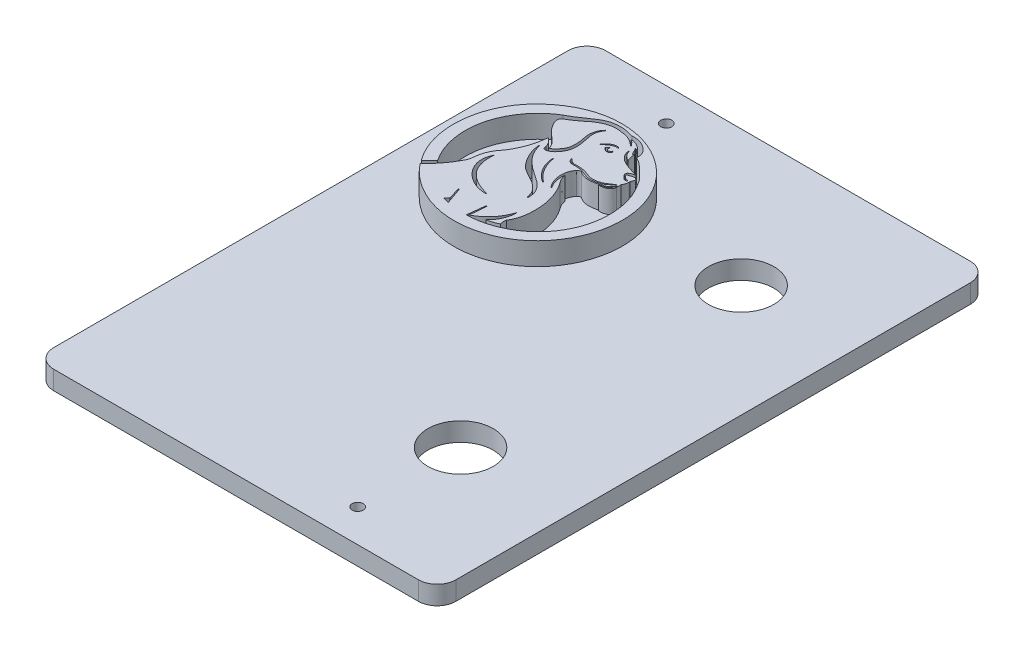
SolidWorks part; units mm, degrees
ref_plane "Alzado" through (0, 0, 0) normal (0, 0, 1) x (1, 0, 0)
ref_plane "Planta" through (0, 0, 0) normal (0, 1, 0) x (1, 0, 0)
ref_plane "Vista lateral" through (0, 0, 0) normal (1, 0, 0) x (0, 0, -1)
sketch "Croquis1" plane through (0, 0, 0) normal (0, 1, 0) x (1, 0, 0)
  line L1 (-19.5, 29.5) -> (19.5, 29.5)
  line L2 (-21.5, 27.5) -> (-21.5, -27.5)
  line L3 (-19.5, -29.5) -> (19.5, -29.5)
  line L4 (21.5, 27.5) -> (21.5, -27.5)
  arc A0 (-19.5, 29.5) -> (-21.5, 27.5) centre (-19.5, 27.5) ccw
  arc A1 (-21.5, -27.5) -> (-19.5, -29.5) centre (-19.5, -27.5) ccw
  arc A2 (19.5, -29.5) -> (21.5, -27.5) centre (19.5, -27.5) ccw
  arc A3 (21.5, 27.5) -> (19.5, 29.5) centre (19.5, 27.5) ccw
  point P4 (0, 29.5)
  point P6 (-21.5, 0)
  point P9 (-21.5, 29.5)
  point P14 (21.5, -29.5)
  point P17 (21.5, 29.5)
  dimension "D3" = 2
  dimension "D1" = 43
  dimension "D2" = 59
extrude "Saliente-Extruir1" add sketch "Croquis1" along normal blind 2
sketch "Croquis2" plane through (0, 2, 0) normal (0, 1, 0) x (1, 0, 0)
  line L1 (-20, 28) -> (20, 28) construction
  line L2 (-20, 28) -> (-20, -28) construction
  line L3 (-20, -28) -> (20, -28) construction
  line L4 (20, 28) -> (20, -28) construction
  line L5 (-11.5, 28) -> (-7.5, 28) construction
  line L6 (-11.5, 28) -> (-11.5, 24) construction
  line L7 (-11.5, 24) -> (-7.5, 24) construction
  line L8 (-7.5, 28) -> (-7.5, 24) construction
  line L9 (7.5, -24) -> (11.5, -24) construction
  line L10 (7.5, -24) -> (7.5, -28) construction
  line L11 (7.5, -28) -> (11.5, -28) construction
  line L12 (11.5, -24) -> (11.5, -28) construction
  circle A0 centre (-9.5, 26) radius 0.6
  circle A1 centre (9.5, -26) radius 0.6
  point P4 (0, 28)
  point P6 (-20, 0)
  point P20 (-7.5, 26)
  point P22 (-9.5, 24)
  point P24 (9.5, -24)
  point P26 (11.5, -26)
  dimension "D9" = 1.2
  dimension "D1" = 40
  dimension "D2" = 56
  dimension "D3" = 8.5
  dimension "D4" = 4
  dimension "D5" = 4
  dimension "D6" = 8.5
  dimension "D7" = 4
  dimension "D8" = 4
extrude "Cortar-Extruir1" cut sketch "Croquis2" against normal up to next
sketch "Croquis4" plane through (0, 2, 0) normal (0, 1, 0) x (1, 0, 0)
  line L0 (-122.7375, -50.7981) -> (530.5958, -50.7981) construction
  line L5 (-21.5, 27.5) -> (-21.5, -27.5)
  line L6 (-19.5, -29.5) -> (19.5, -29.5)
  line L7 (-16.785, 7.0935) -> (-15.9113, 7.9672)
  line L8 (-5.5288, 19.0738) -> (-5.5288, 18.8353)
  line L9 (-9.3335, 4.4566) -> (-9.1235, 6.3465)
  line L10 (-9.1235, 6.3465) -> (-9.0335, 6.3465)
  line L11 (-6.8581, 7.3327) -> (-6.8085, 7.3327)
  line L12 (-12.0774, 4.7929) -> (-11.4431, 4.6194)
  line L13 (-11.4431, 4.6194) -> (-12.0774, 6.4316)
  line L14 (-12.0774, 6.4316) -> (-12.1399, 6.4316)
  line L15 (-12.1399, 6.4316) -> (-12.1399, 6.3795)
  line L16 (-12.1399, 6.3795) -> (-11.7982, 5.1609)
  line L17 (-11.7982, 5.1609) -> (-12.0774, 4.7929)
  line L18 (-9.9359, 14.2979) -> (-9.8725, 14.2979)
  line L19 (-8.1359, 18.1188) -> (-7.8727, 18.382)
  line L20 (-7.8727, 18.382) -> (-7.8727, 18.1188)
  line L21 (-7.3858, 18.1819) -> (-7.3106, 18.0255)
  line L22 (21.5, -27.5) -> (21.5, 27.5)
  line L23 (19.5, 29.5) -> (-19.5, 29.5)
  line L24 (-21.5, 27.5) -> (-21.5, -27.5)
  line L25 (-19.5, -29.5) -> (19.5, -29.5)
  line L26 (21.5, -27.5) -> (21.5, 27.5)
  line L27 (19.5, 29.5) -> (-19.5, 29.5)
  arc A4 (-19.5, 29.5) -> (-21.5, 27.5) centre (-19.5, 27.5) ccw
  arc A5 (-21.5, -27.5) -> (-19.5, -29.5) centre (-19.5, -27.5) ccw
  arc A6 (19.5, -29.5) -> (21.5, -27.5) centre (19.5, -27.5) ccw
  arc A7 (21.5, 27.5) -> (19.5, 29.5) centre (19.5, 27.5) ccw
  arc A8 (-19.5, 29.5) -> (-21.5, 27.5) centre (-19.5, 27.5) ccw
  arc A9 (-21.5, -27.5) -> (-19.5, -29.5) centre (-19.5, -27.5) ccw
  arc A10 (19.5, -29.5) -> (21.5, -27.5) centre (19.5, -27.5) ccw
  arc A11 (21.5, 27.5) -> (19.5, 29.5) centre (19.5, 27.5) ccw
  spline S0 degree 3 poles (-16.5632, 6.7375) (-14.8698, 4.5668) (-10.3045, 2.3343) (-4.2027, 4.3505) (-1.3009, 7.9071) (-0.3267, 11.4069) (-0.6253, 14.6622) (-2.3476, 18.3583) (-6.4582, 21.3167) (-11.5601, 21.333) (-14.6523, 19.63) (-18.7115, 15.7796) (-19.2435, 10.4242) (-16.785, 7.0935) knots 0 0 0 0 0.147574 0.250522 0.323508 0.389308 0.443163 0.498041 0.607268 0.697259 0.760333 0.794706 1 1 1 1
  spline S1 degree 3 poles (-15.9113, 7.9672) (-17.022, 9.5861) (-17.9024, 13.9923) (-15.3035, 17.7268) (-13.4018, 18.8576) knots 0 0 0 0 0.471177 1 1 1 1
  spline S2 degree 3 poles (-13.4018, 18.8576) (-12.7034, 19.2015) (-11.9134, 19.8024) (-10.819, 20.5175) (-10.1633, 20.7932) (-9.3139, 20.8775) (-8.5496, 20.8571) (-8.0007, 20.6262) (-7.7837, 20.6096) knots 0 0 0 0 0.376488 0.480607 0.636086 0.714834 0.894869 1 1 1 1
  spline S3 degree 3 poles (-7.7837, 20.6096) (-7.2847, 20.6655) (-6.3122, 20.4163) (-5.5036, 19.6001) (-5.5288, 19.0738) knots 0 0 0 0 0.492815 1 1 1 1
  spline S4 degree 3 poles (-5.5288, 18.8353) (-4.8157, 18.5464) (-4.2736, 17.8154) (-3.5047, 17.1835) (-3.2294, 16.83) (-2.9589, 16.3955) (-2.3912, 15.4856) (-1.5721, 13.313) (-1.6756, 9.9883) (-4.0229, 5.9119) (-7.2629, 4.465) (-9.3335, 4.4566) knots 0 0 0 0 0.110187 0.134978 0.149215 0.177412 0.212079 0.310623 0.523348 0.686566 1 1 1 1
  spline S5 degree 2 poles (-9.0335, 6.3465) (-9.0409, 5.4473) (-9.2065, 4.5608) knots 0 0 0 1 1 1
  spline S6 degree 2 poles (-9.2065, 4.5608) (-7.4402, 5.4889) (-6.8581, 7.3327) knots 0 0 0 1 1 1
  spline S7 degree 2 poles (-6.8085, 7.3327) (-6.8699, 5.9452) (-7.836, 5.0481) knots 0 0 0 1 1 1
  spline S8 degree 2 poles (-7.836, 5.0481) (-7.2192, 5.1489) (-6.6627, 5.4281) knots 0 0 0 1 1 1
  spline S9 degree 2 poles (-6.6627, 5.4281) (-6.7692, 5.7768) (-6.6959, 6.1282) knots 0 0 0 1 1 1
  spline S10 degree 3 poles (-6.6959, 6.1282) (-6.2762, 6.7324) (-5.8324, 9.0145) (-6.4174, 11.2128) (-7.3106, 12.4547) knots 0 0 0 0 0.330119 1 1 1 1
  spline S11 degree 2 poles (-7.3106, 12.4547) (-7.6354, 12.8775) (-7.7296, 13.4064) knots 0 0 0 1 1 1
  spline S12 degree 2 poles (-7.7296, 13.4064) (-7.8488, 12.3837) (-7.3106, 11.573) knots 0 0 0 1 1 1
  spline S13 degree 2 poles (-7.3106, 11.573) (-7.3003, 11.4896) (-7.3858, 11.5376) knots 0 0 0 1 1 1
  spline S14 degree 3 poles (-7.3858, 11.5376) (-8.0043, 12.3436) (-8.2288, 13.603) (-7.5631, 14.4371) knots 0 0 0 0 1 1 1 1
  spline S15 degree 2 poles (-7.5631, 14.4371) (-7.3127, 14.7203) (-7.0836, 14.536) knots 0 0 0 1 1 1
  spline S16 degree 3 poles (-7.0836, 14.536) (-6.3339, 14.0187) (-5.3783, 14.2313) (-4.5915, 14.536) knots 0 0 0 0 1 1 1 1
  spline S17 degree 2 poles (-4.5915, 14.536) (-4.1033, 14.7457) (-3.9341, 15.2267) knots 0 0 0 1 1 1
  spline S18 degree 2 poles (-3.9341, 15.2267) (-3.8865, 15.1779) (-3.8989, 15.1117) knots 0 0 0 1 1 1
  spline S19 degree 2 poles (-3.8989, 15.1117) (-4.2277, 14.3446) (-5.0322, 14.2979) knots 0 0 0 1 1 1
  spline S20 degree 3 poles (-5.0322, 14.2979) (-4.5724, 14.2132) (-3.8869, 14.471) (-3.8418, 14.9957) knots 0 0 0 0 1 1 1 1
  spline S21 degree 2 poles (-3.8418, 14.9957) (-3.8308, 15.2492) (-3.8467, 15.5021) knots 0 0 0 1 1 1
  spline S22 degree 3 poles (-3.8467, 15.5021) (-3.7634, 15.705) (-3.6432, 15.9167) (-3.6572, 16.1455) knots 0 0 0 0 1 1 1 1
  spline S23 degree 1 poles (-3.6572, 16.1455) (-3.6599, 16.2812) knots 0 0 1 1
  spline S24 degree 3 poles (-3.6599, 16.2812) (-3.6397, 16.3541) (-3.4183, 16.7278) (-3.7266, 16.9131) (-4.0125, 16.8999) (-4.2438, 16.7809) (-4.4582, 16.7436) (-4.4694, 16.598) (-4.4202, 16.5613) knots 0 0 0 0 0.337179 0.394734 0.627403 0.822679 0.889477 1 1 1 1
  spline S25 degree 2 poles (-4.4202, 16.5613) (-4.2544, 16.3024) (-3.9826, 16.2812) knots 0 0 0 1 1 1
  spline S26 degree 2 poles (-3.9826, 16.2812) (-3.8354, 16.2666) (-3.8811, 16.1455) knots 0 0 0 1 1 1
  spline S27 degree 2 poles (-3.8811, 16.1455) (-4.2038, 16.1041) (-4.4202, 16.3746) knots 0 0 0 1 1 1
  spline S28 degree 3 poles (-4.4202, 16.3746) (-4.5142, 16.4542) (-4.8847, 16.9441) (-4.1459, 17.1657) (-3.9826, 17.1585) knots 0 0 0 0 0.378361 1 1 1 1
  spline S29 degree 2 poles (-3.9826, 17.1585) (-3.8853, 17.1681) (-4.0272, 17.2135) knots 0 0 0 1 1 1
  spline S30 degree 3 poles (-4.0272, 17.2135) (-4.9307, 17.4847) (-6.4573, 17.7911) (-6.5593, 19.0352) knots 0 0 0 0 1 1 1 1
  spline S31 degree 2 poles (-6.5593, 19.0352) (-6.5653, 19.0731) (-6.5285, 19.0738) knots 0 0 0 1 1 1
  spline S32 degree 2 poles (-6.5285, 19.0738) (-6.3095, 18.3722) (-5.7032, 18.1188) knots 0 0 0 1 1 1
  spline S33 degree 2 poles (-5.7032, 18.1188) (-5.9182, 18.5518) (-5.9205, 19.0352) knots 0 0 0 1 1 1
  spline S34 degree 3 poles (-5.9205, 19.0352) (-5.9414, 18.9977) (-5.9717, 18.9606) (-6.0549, 18.9186) (-6.0885, 18.9799) (-6.0953, 18.9973) knots 0 0 0 0 0.479864 0.649423 1 1 1 1
  spline S35 degree 3 poles (-6.0953, 18.9973) (-6.2442, 19.1706) (-6.2584, 19.4159) (-6.424, 19.5789) knots 0 0 0 0 1 1 1 1
  spline S36 degree 3 poles (-6.424, 19.5789) (-6.4429, 19.5908) (-6.4489, 19.6296) (-6.4134, 19.656) (-6.3637, 19.6422) (-6.1612, 19.5076) (-6.0014, 19.2796) (-5.9205, 19.1129) knots 0 0 0 0 0.081296 0.094197 0.154111 0.241243 1 1 1 1
  spline S37 degree 2 poles (-5.9205, 19.1129) (-5.9062, 19.2703) (-6.0094, 19.3953) knots 0 0 0 1 1 1
  spline S38 degree 3 poles (-6.0094, 19.3953) (-6.3386, 19.8465) (-6.9075, 20.2571) (-7.4959, 20.2193) knots 0 0 0 0 1 1 1 1
  spline S39 degree 3 poles (-7.4959, 20.2193) (-7.3495, 20.2605) (-6.3946, 19.1326) (-7.2439, 19.8702) knots 0 0 0 0 1 1 1 1
  spline S40 degree 2 poles (-7.2439, 19.8702) (-7.9077, 20.3674) (-8.6869, 20.4004) knots 0 0 0 1 1 1
  spline S41 degree 3 poles (-8.6869, 20.4004) (-9.8525, 20.692) (-10.9797, 20.0855) (-11.7982, 19.3264) knots 0 0 0 0 1 1 1 1
  spline S42 degree 3 poles (-11.7982, 19.3264) (-12.1142, 19.0878) (-12.5297, 18.7746) (-13.0385, 18.5179) (-13.2503, 18.3528) (-13.3056, 17.9054) (-13.0112, 17.344) (-12.5111, 16.6481) (-11.6883, 16.0347) (-11.1639, 15.4466) (-11.0758, 14.9957) knots 0 0 0 0 0.204538 0.261311 0.295484 0.335428 0.47711 0.607279 0.774102 1 1 1 1
  spline S43 degree 3 poles (-11.0758, 14.9957) (-10.626, 15.3034) (-10.0547, 15.9244) (-10.0292, 16.9143) (-10.0579, 17.5026) (-10.3347, 18.4881) (-10.1473, 19.2988) (-9.7318, 19.7195) knots 0 0 0 0 0.334112 0.413274 0.565311 0.671298 1 1 1 1
  spline S44 degree 2 poles (-9.7318, 19.7195) (-9.6204, 19.7685) (-9.7169, 19.6085) knots 0 0 0 1 1 1
  spline S45 degree 3 poles (-9.7169, 19.6085) (-10.1978, 18.9659) (-9.814, 17.7875) (-9.6467, 16.2658) (-10.2358, 15.1645) (-10.7694, 14.6149) (-11.2817, 14.6949) knots 0 0 0 0 0.336613 0.675632 0.736003 1 1 1 1
  spline S46 degree 2 poles (-11.2817, 14.6949) (-11.399, 14.8323) (-11.3943, 15.0198) knots 0 0 0 1 1 1
  spline S47 degree 2 poles (-11.3943, 15.0198) (-11.5795, 15.6217) (-12.1011, 15.9692) knots 0 0 0 1 1 1
  spline S48 degree 2 poles (-12.1011, 15.9692) (-12.2605, 14.0891) (-13.269, 12.5401) knots 0 0 0 1 1 1
  spline S49 degree 3 poles (-13.269, 12.5401) (-13.6836, 12.0372) (-14.3255, 11.0354) (-14.2762, 9.8711) (-14.4933, 9.4536) knots 0 0 0 0 0.588641 1 1 1 1
  spline S50 degree 2 poles (-14.4933, 9.4536) (-15.277, 7.9064) (-16.5632, 6.7375) knots 0 0 0 1 1 1
  spline S51 degree 3 poles (-13.3645, 11.4928) (-14.4163, 9.4438) (-12.2608, 7.4695) (-10.362, 7.461) knots 0 0 0 0 1 1 1 1
  spline S52 degree 3 poles (-10.362, 7.461) (-10.3525, 7.4448) (-10.1832, 7.4813) (-10.2873, 7.5258) knots 0 0 0 0 1 1 1 1
  spline S53 degree 2 poles (-10.2873, 7.5258) (-13.7085, 8.4413) (-13.3645, 11.4928) knots 0 0 0 1 1 1
  spline S54 degree 3 poles (-10.8023, 12.2503) (-10.4075, 11.7763) (-9.0782, 11.2292) (-7.8384, 10.2869) (-7.7296, 9.3633) knots 0 0 0 0 0.409621 1 1 1 1
  spline S55 degree 2 poles (-7.7296, 9.3633) (-7.6927, 9.3381) (-7.6487, 9.3466) knots 0 0 0 1 1 1
  spline S56 degree 3 poles (-7.6487, 9.3466) (-7.5865, 9.9793) (-8.0642, 10.953) (-10.0666, 12.2137) (-11.5007, 13.3109) (-11.8131, 14.7402) knots 0 0 0 0 0.255348 0.427023 1 1 1 1
  spline S57 degree 2 poles (-10.8023, 12.2503) (-11.7648, 13.3878) (-11.8959, 14.7981) knots 0 0 0 1 1 1
  spline S58 degree 2 poles (-11.8131, 14.7402) (-11.8434, 14.785) (-11.8959, 14.7981) knots 0 0 0 1 1 1
  spline S59 degree 3 poles (-9.9359, 14.2979) (-9.9052, 13.1704) (-9.2295, 12.1471) (-8.2928, 11.573) knots 0 0 0 0 1 1 1 1
  spline S60 degree 3 poles (-8.2928, 11.573) (-8.2312, 11.585) (-8.2885, 11.6616) (-8.316, 11.6743) knots 0 0 0 0 1 1 1 1
  spline S61 degree 3 poles (-8.316, 11.6743) (-8.9262, 12.1185) (-9.5532, 12.9992) (-9.8372, 14.0054) (-9.8725, 14.2979) knots 0 0 0 0 0.717863 1 1 1 1
  spline S62 degree 2 poles (-8.9229, 15.3268) (-8.8397, 14.8647) (-8.4122, 14.7981) knots 0 0 0 1 1 1
  spline S63 degree 2 poles (-8.4122, 14.7981) (-7.896, 14.8324) (-7.3858, 14.7552) knots 0 0 0 1 1 1
  spline S64 degree 3 poles (-7.3858, 14.7552) (-7.1304, 14.6827) (-6.8074, 14.5264) (-6.376, 14.3854) (-6.1128, 14.3531) (-5.8353, 14.3445) (-5.5304, 14.3973) (-5.0862, 14.48) (-4.6174, 14.7229) (-3.5737, 15.6598) (-4.6046, 14.9008) (-5.0762, 14.6593) (-5.6068, 14.4893) (-6.2321, 14.5156) (-6.8105, 14.7714) (-7.3379, 14.9164) (-7.8891, 14.9491) (-8.4728, 14.8708) (-8.7968, 15.1912) (-8.9229, 15.3268) knots 0 0 0 0 0.087377 0.118286 0.149286 0.174627 0.209512 0.251955 0.31871 0.414243 0.511635 0.549469 0.60905 0.687936 0.75107 0.81673 0.866879 0.934436 1 1 1 1
  spline S65 degree 2 poles (-7.8727, 18.1188) (-7.6746, 17.782) (-7.3858, 18.1819) knots 0 0 0 1 1 1
  spline S66 degree 3 poles (-7.3106, 18.0255) (-7.4649, 17.6619) (-8.0277, 17.7962) (-8.1359, 18.1188) knots 0 0 0 0 1 1 1 1
  spline S67 degree 3 poles (-8.7379, 18.1188) (-8.3417, 18.3486) (-7.8759, 18.9315) (-7.3106, 18.6895) knots 0 0 0 0 1 1 1 1
  spline S68 degree 3 poles (-8.7379, 18.1188) (-8.4996, 18.4043) (-8.0871, 18.9555) (-7.4102, 18.8637) (-7.3106, 18.6895) knots 0 0 0 0 0.684259 1 1 1 1
  dimension "D1" = 0
extrude "Saliente-Extruir2" add sketch "Croquis4" along normal blind 2.4 contours S49 S50 S0 L7 S1 S2 S3 L8 S4 L9 L10 S5 S6 L11 S7 S8 S9 S10 S11 S12 S13 S14 S15 S16 S17 S18 S19 S20 S21 S22 S23 S24 S25 S26 S27 S28 S29 S30 S31 S32 S33 S34 S35 S36 S37 S38 S39 S40 S41 S42 S43
sketch "Croquis5" plane through (0, 2, 0) normal (0, 1, 0) x (1, 0, 0)
  line L0 (-25.224, 0) -> (25.0409, 0) construction
  line L2 (-20, -28) -> (20, -28) construction
  line L3 (-20, -28) -> (-20, 28) construction
  line L4 (-20, 28) -> (20, 28) construction
  line L5 (20, -28) -> (20, 28) construction
  circle A0 centre (9.5, -15) radius 3.5
  circle A1 centre (9.5, 15) radius 3.5
  point P9 (0, 28)
  point P10 (-20, 0)
  dimension "D1" = 7
  dimension "D2" = 15
  dimension "D3" = 40
  dimension "D4" = 56
  dimension "D5" = 10.5
  dimension "D6" = 10.5
  dimension "D7" = 15
extrude "Cortar-Extruir2" cut sketch "Croquis5" against normal up to next
